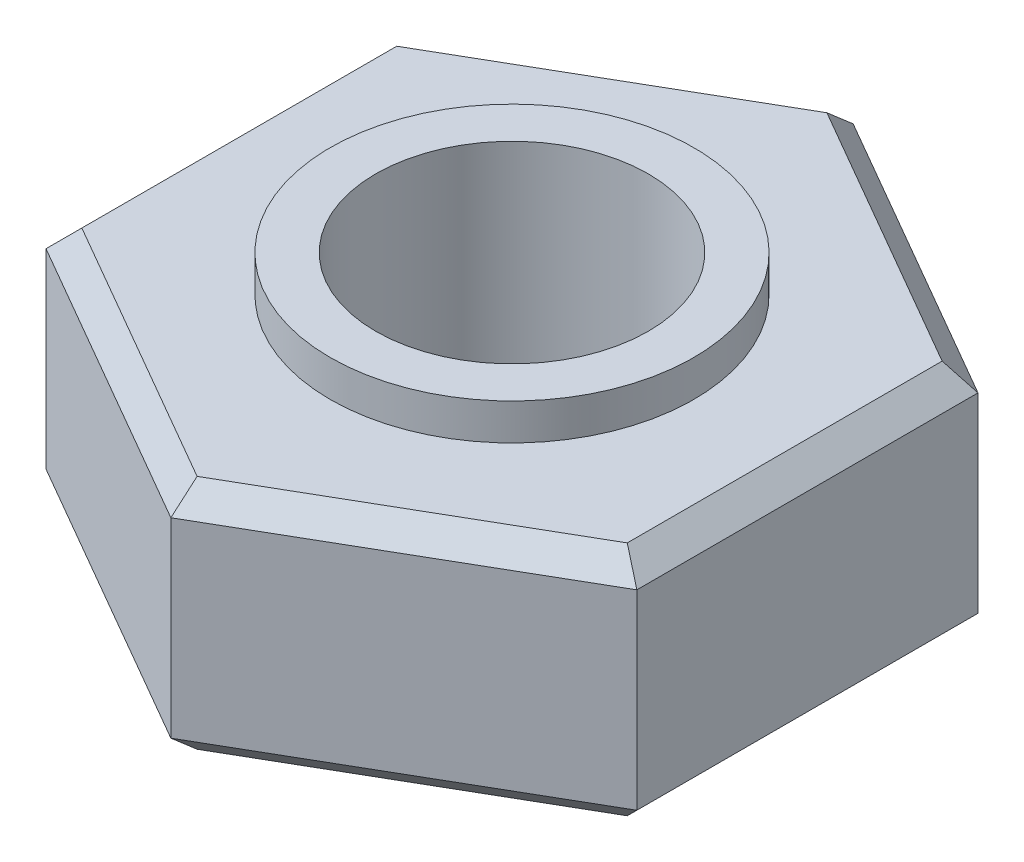
SolidWorks part; units mm, degrees
ref_plane "Front Plane" through (0, 0, 0) normal (0, 0, 1) x (1, 0, 0)
ref_plane "Top Plane" through (0, 0, 0) normal (0, 1, 0) x (1, 0, 0)
ref_plane "Right Plane" through (0, 0, 0) normal (1, 0, 0) x (0, 0, -1)
sketch "Sketch1" plane through (0, 0, 0) normal (0, 1, 0) x (1, 0, 0)
  line L1 (0, -7.5056) -> (6.5, -3.7528)
  line L2 (6.5, -3.7528) -> (6.5, 3.7528)
  line L3 (6.5, 3.7528) -> (0, 7.5056)
  line L4 (0, 7.5056) -> (-6.5, 3.7528)
  line L5 (-6.5, 3.7528) -> (-6.5, -3.7528)
  line L6 (-6.5, -3.7528) -> (0, -7.5056)
  circle A0 centre (0, 0) radius 6.5 construction
  circle A1 centre (0, 0) radius 3
  dimension "D2" = 6
  dimension "D1" = 13
extrude "Boss-Extrude1" add sketch "Sketch1" along normal blind 6
sketch "Sketch3" plane through (0, 6, 0) normal (0, 1, 0) x (1, 0, 0)
  line L6 (-6.5, -3.7528) -> (0, -7.5056)
  line L7 (0, -7.5056) -> (6.5, -3.7528)
  line L8 (6.5, -3.7528) -> (6.5, 3.7528)
  line L9 (6.5, 3.7528) -> (0, 7.5056)
  line L10 (0, 7.5056) -> (-6.5, 3.7528)
  line L11 (-6.5, 3.7528) -> (-6.5, -3.7528)
  line L12 (-6.5, -3.7528) -> (0, -7.5056)
  line L13 (0, -7.5056) -> (6.5, -3.7528)
  line L14 (6.5, -3.7528) -> (6.5, 3.7528)
  line L15 (6.5, 3.7528) -> (0, 7.5056)
  line L16 (0, 7.5056) -> (-6.5, 3.7528)
  line L17 (-6.5, 3.7528) -> (-6.5, -3.7528)
  circle A2 centre (0, 0) radius 4
  dimension "D2" = 8
  dimension "D1" = 0
extrude "Cut-Extrude1" cut sketch "Sketch3" against normal blind 0.8
chamfer "Chamfer1" distance 0.5 angle 45 12 edges at (-6.5, 0, 0) (-3.25, 0, -5.6292) (3.25, 0, -5.6292) (6.5, 0, 0) (-3.25, 0, 5.6292) (3.25, 0, 5.6292) (-3.25, 5.2, -5.6292) (3.25, 5.2, -5.6292) (6.5, 5.2, 0) (3.25, 5.2, 5.6292) (-3.25, 5.2, 5.6292) (-6.5, 5.2, 0)
